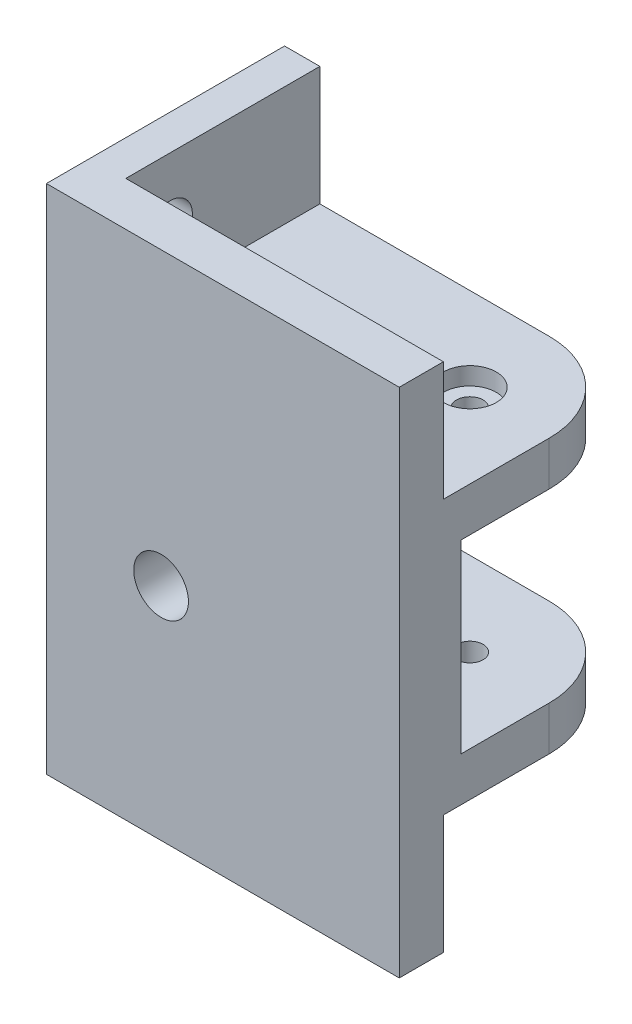
SolidWorks part; units mm, degrees
ref_plane "前视基准面" through (0, 0, 0) normal (0, 0, 1) x (1, 0, 0)
ref_plane "上视基准面" through (0, 0, 0) normal (0, 1, 0) x (1, 0, 0)
ref_plane "右视基准面" through (0, 0, 0) normal (1, 0, 0) x (0, 0, -1)
other "Configuration Table"
sketch "草图1" plane through (0, 0, 0) normal (0, 1, 0) x (1, 0, 0)
  line L0 (-20, 13.5) -> (5, 13.5)
  line L1 (20, -1.5) -> (20, -13.5)
  line L6 (-20, -13.5) -> (20, -13.5)
  line L7 (-20, -13.5) -> (-20, 13.5)
  arc A0 (20, -1.5) -> (5, 13.5) centre (5, -1.5) ccw
extrude "凸台-拉伸1" add sketch "草图1" along normal blind 58 contours L1 L6 L7 L0 A0
sketch "草图2" plane through (0, 0, 13.5) normal (0, 0, 1) x (1, 0, 0)
  circle A0 centre (-7, 33) radius 3
extrude "切除-拉伸1" cut sketch "草图2" against normal blind 58 contours A0
sketch "草图3" plane through (0, 0, -13.5) normal (0, 0, -1) x (-1, 0, 0)
  line L0 (20, 58) -> (20, 0)
  line L1 (20, 29) -> (-5, 29)
  line L2 (-5, 58) -> (-5, 0) construction
  line L3 (-5, 29) -> (-5, 43.5)
  line L4 (-5, 29) -> (-5, 14.5)
  line L5 (-5, 43.5) -> (20, 43.5)
  line L6 (-5, 14.5) -> (20, 14.5)
  line L7 (20, 43.5) -> (-20, 43.5)
  line L8 (20, 43.5) -> (20, 58)
  line L9 (20, 58) -> (-20, 58)
  line L10 (-20, 43.5) -> (-20, 58)
  line L12 (20, 14.5) -> (-20, 14.5)
  line L13 (20, 14.5) -> (20, 0)
  line L14 (20, 0) -> (-20, 0)
  line L15 (-20, 14.5) -> (-20, 0)
  line M8 (-5, 0) -> (20, 0)
  line M9 (20, 0) -> (20, 58)
  line M10 (20, 58) -> (-5, 58)
  line M11 (-5, 58) -> (-5, 0)
extrude "切除-拉伸2" cut sketch "草图3" against normal blind 22 contours L10 L7 L9 M11 | L12 L15 L14 M11 | L6 M11 M8 M9 | L5 M11 M9 M10
sketch "草图5" plane through (0, 0, 8.5) normal (0, 0, -1) x (-1, 0, 0)
  line L0 (20, 43.5) -> (-5, 43.5) construction
  line L1 (20, 58) -> (16, 58)
  line L2 (20, 58) -> (20, 43.5)
  line L3 (20, 43.5) -> (16, 43.5)
  line L4 (16, 58) -> (16, 43.5)
  line L5 (20, 14.5) -> (-5, 14.5) construction
  line L6 (20, 0) -> (16, 0)
  line L7 (20, 0) -> (20, 14.5)
  line L8 (20, 14.5) -> (16, 14.5)
  line L9 (16, 0) -> (16, 14.5)
extrude "凸台-拉伸2" add sketch "草图5" along normal blind 22 contours L9 L6 L7 L8 | L2 L1 L4 L3
sketch "草图8" plane through (-20, 0, 0) normal (-1, 0, 0) x (0, 0, 1)
  line L0 (13.5, 58) -> (3.5, 58)
  line L2 (-13.5, 58) -> (8.5, 58) construction
  line L3 (3.5, 58) -> (3.5, 43.5)
  line L4 (8.5, 43.5) -> (1.5, 43.5) construction
  line L5 (13.5, 0) -> (3.5, 0)
  line L6 (-13.5, 0) -> (8.5, 0) construction
  line L7 (3.5, 0) -> (3.5, 14.5)
  line L8 (8.5, 14.5) -> (1.5, 14.5) construction
  circle A0 centre (3.5, 50.75) radius 2.55
  circle A1 centre (3.5, 7.25) radius 2.55
extrude "切除-拉伸3" cut sketch "草图8" against normal blind 22 contours L3 A0 | L3 A0 | L7 A1 | L7 A1
sketch "草图10" plane through (0, 43.5, 0) normal (0, 1, 0) x (1, 0, 0)
  line L0 (20, -13.5) -> (20, -6.5)
  line L1 (20, -8.5) -> (20, -1.5) construction
  line L6 (20, 13.5) -> (20, -6.5)
  line L8 (-16, 13.5) -> (5, 13.5) construction
  line L9 (0, 13.5) -> (20, 13.5)
  arc A0 (20, -6.5) -> (0, 13.5) centre (20, 13.5) cw
  line M9 (5, 13.5) -> (-16, 13.5)
  line M12 (20, -8.5) -> (20, -1.5)
  arc M13 (20, -1.5) -> (5, 13.5) centre (5, -1.5) ccw
extrude "切除-拉伸4" cut sketch "草图10" against normal blind 30 contours A0 M12 M13 M9 | L9 L6 M13
sketch "草图11" plane through (0, 43.5, 0) normal (0, 1, 0) x (1, 0, 0)
  line L0 (0, 13.5) -> (5, 13.5)
  line L2 (20, -1.5) -> (20, -6.5)
  arc A0 (5, 13.5) -> (20, -1.5) centre (5, -1.5) cw
  arc A1 (0, 13.5) -> (20, -6.5) centre (20, 13.5) ccw
  arc A2 (0, 13.5) -> (20, -6.5) centre (20, 13.5) ccw construction
  circle A3 centre (9.5, 4) radius 1.51
  arc M15 (20, -6.5) -> (0, 13.5) centre (20, 13.5) cw
extrude "凸台-拉伸5" add sketch "草图11" against normal blind 4 contours A0 L0 L2 A3 M15
sketch "草图13" plane through (0, 14.5, 0) normal (0, -1, 0) x (1, 0, 0)
  line L0 (0, -13.5) -> (5, -13.5)
  line L2 (20, 6.5) -> (20, 1.5)
  arc A0 (0, -13.5) -> (20, 6.5) centre (20, -13.5) cw
  arc A1 (20, 1.5) -> (5, -13.5) centre (5, 1.5) cw
extrude "凸台-拉伸6" add sketch "草图13" against normal blind 4 contours A1 L2 A0 L0
sketch "草图17" plane through (0, 43.5, 0) normal (0, 1, 0) x (1, 0, 0)
  line L0 (20, -1.5) -> (20, 13.5)
  line L1 (20, -1.5) -> (20, -6.5)
  line L2 (20, -8.5) -> (20, -1.5) construction
  line L3 (-16, 13.5) -> (5, 13.5) construction
  line L4 (0, 13.5) -> (20, 13.5)
  line L6 (5.8579, -0.6421) -> (12.9289, 6.4289)
  arc A0 (20, -6.5) -> (0, 13.5) centre (20, 13.5) cw
  circle A1 centre (12.9289, 6.4289) radius 1.51
sketch "草图18" plane through (0, 0, 13.5) normal (0, 0, 1) x (1, 0, 0)
  circle A0 centre (-7, 33) radius 3.05
extrude "切除-拉伸7" cut sketch "草图18" against normal blind 50
extrude "切除-拉伸8" cut sketch "草图17" against normal blind 50
sketch "草图19" plane through (0, 43.5, 0) normal (0, 1, 0) x (1, 0, 0)
  line L2 (10, 13.5) -> (5, 13.5)
  line L3 (20, 3.5) -> (20, -1.5)
  arc A0 (5, 13.5) -> (20, -1.5) centre (5, -1.5) cw
  arc A1 (10, 13.5) -> (20, 3.5) centre (10, 3.5) cw
extrude "凸台-拉伸7" add sketch "草图19" against normal blind 4 contours L3 A0 L2 A1
sketch "草图20" plane through (0, 43.5, 0) normal (0, 1, 0) x (1, 0, 0)
  line L2 (20, 3.5) -> (20, -8.5)
  line L3 (20, -8.5) -> (-16, -8.5)
  line L4 (-16, -8.5) -> (-16, 13.5)
  line L5 (-16, 13.5) -> (10, 13.5)
  arc A0 (10, 13.5) -> (20, 3.5) centre (10, 3.5) cw
  arc A1 (20, 3.5) -> (10, 13.5) centre (10, 3.5) ccw construction
  circle A2 centre (12.9289, 6.4289) radius 1.51
extrude "凸台-拉伸8" add sketch "草图20" along normal blind 1 contours A0 L2 L3 L4 L5
sketch "草图21" plane through (0, 44.5, 0) normal (0, 1, 0) x (1, 0, 0)
  circle A0 centre (12.9289, 6.4289) radius 3
  circle M2 centre (12.9289, 6.4289) radius 1.51
extrude "切除-拉伸9" cut sketch "草图21" against normal blind 2 contours A0 M2
sketch "草图22" plane through (0, 14.5, 0) normal (0, -1, 0) x (-1, 0, 0)
  line L0 (-5, 13.5) -> (-10, 13.5)
  line L1 (-20, -1.5) -> (-20, 3.5)
  arc A0 (-10, 13.5) -> (-20, 3.5) centre (-10, 3.5) ccw
  arc A1 (-5, 13.5) -> (-20, -1.5) centre (-5, -1.5) ccw
  arc A2 (-5, 13.5) -> (-20, -1.5) centre (-5, -1.5) ccw construction
extrude "凸台-拉伸9" add sketch "草图22" against normal blind 4 contours L0 A0 L1 A1
sketch "草图23" plane through (0, 14.5, 0) normal (0, -1, 0) x (-1, 0, 0)
  line L0 (16, -8.5) -> (16, 13.5)
  line L1 (16, 13.5) -> (-10, 13.5)
  line L4 (-20, 3.5) -> (-20, -8.5)
  line L5 (-20, -8.5) -> (16, -8.5)
  arc A0 (-10, 13.5) -> (-20, 3.5) centre (-10, 3.5) ccw
  arc A1 (-10, 13.5) -> (-20, 3.5) centre (-10, 3.5) ccw construction
  circle A2 centre (-12.9289, 6.4289) radius 1.51
extrude "凸台-拉伸10" add sketch "草图23" along normal blind 1 contours A0 L4 L5 L0 L1
sketch "草图24" plane through (0, 13.5, 0) normal (0, -1, 0) x (-1, 0, 0)
  circle A0 centre (-12.9289, 6.4289) radius 3
extrude "切除-拉伸10" cut sketch "草图24" against normal blind 2
sketch "草图25" plane through (0, 0, 13.5) normal (0, 0, 1) x (1, 0, 0)
  line L0 (-7, 29) -> (-20, 29)
  line L1 (-20, 58) -> (20, 58) construction
  line L2 (-7, 58) -> (-7, 0)
  line L3 (-20, 0) -> (20, 0) construction
  line L4 (-20, 58) -> (-20, 0) construction
  circle A1 centre (-7, 33) radius 3.05
  circle A2 centre (-7, 25) radius 3.05
extrude "切除-拉伸11" cut sketch "草图25" against normal blind 100 contours A2 L2 | A2 L2
sketch "草图26" plane through (0, 0, 13.5) normal (0, 0, 1) x (1, 0, 0)
  circle A0 centre (-7, 33) radius 3.05
extrude "凸台-拉伸11" add sketch "草图26" against normal blind 27 contours A0
sketch "草图27" plane through (0, 0, 13.5) normal (0, 0, 1) x (1, 0, 0)
  circle A0 centre (-7, 25) radius 3.1
extrude "切除-拉伸12" cut sketch "草图27" against normal blind 27
sketch "草图29" plane through (0, 0, -13.5) normal (0, 0, -1) x (-1, 0, 0)
  line L1 (0, 39.5) -> (-20, 39.5)
  line L2 (0, 39.5) -> (0, 18.5)
  line L3 (0, 18.5) -> (-20, 18.5)
  line L4 (-20, 39.5) -> (-20, 18.5)
extrude "切除-拉伸13" cut sketch "草图29" against normal blind 20 contours L2 L1 L4 L3
sketch "草图30" plane through (0, 13.5, 0) normal (0, -1, 0) x (-1, 0, 0)
  circle A0 centre (-12.9289, 6.4289) radius 3
extrude "凸台-拉伸12" add sketch "草图30" against normal blind 5 contours A0
sketch "草图32" plane through (0, 44.5, 0) normal (0, 1, 0) x (1, 0, 0)
  circle A0 centre (12.9289, 6.4289) radius 3
extrude "凸台-拉伸13" add sketch "草图32" against normal blind 5 contours A0
sketch "草图34" plane through (0, 44.5, 0) normal (0, 1, 0) x (1, 0, 0)
  line L3 (-16, -8.5) -> (10.5, -8.5)
  line L4 (-16, -8.5) -> (20, -8.5) construction
  line L5 (10.5, -8.5) -> (10.5, 4)
  circle A0 centre (10.5, 4) radius 1.51
extrude "切除-拉伸14" cut sketch "草图34" against normal blind 100
sketch "草图35" plane through (0, 44.5, 0) normal (0, 1, 0) x (1, 0, 0)
  circle A0 centre (10.5, 4) radius 3
extrude "切除-拉伸15" cut sketch "草图35" against normal blind 2
sketch "草图36" plane through (0, 13.5, 0) normal (0, -1, 0) x (-1, 0, 0)
  circle A0 centre (-10.5, 4) radius 3
extrude "切除-拉伸16" cut sketch "草图36" against normal blind 2
